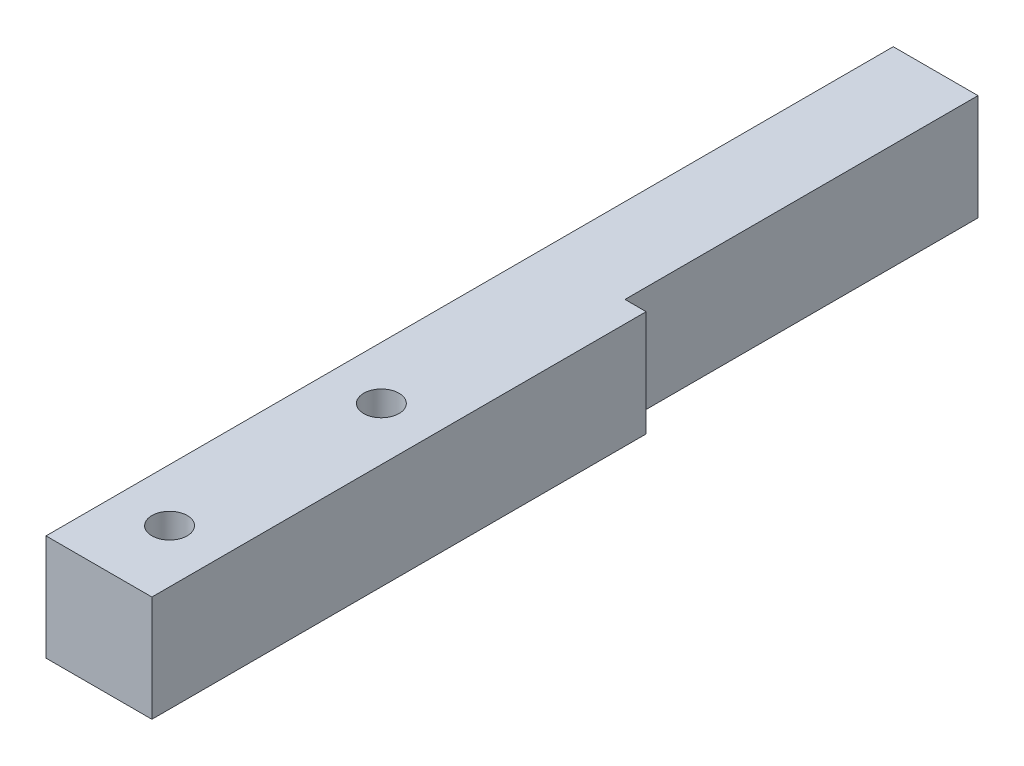
SolidWorks part; units mm, degrees
ref_plane "Front Plane" through (0, 0, 0) normal (0, 0, 1) x (1, 0, 0)
ref_plane "Top Plane" through (0, 0, 0) normal (0, 1, 0) x (1, 0, 0)
ref_plane "Right Plane" through (0, 0, 0) normal (1, 0, 0) x (0, 0, -1)
sketch "Sketch1" plane through (0, 0, 0) normal (0, 0, 1) x (1, 0, 0)
  line L1 (-9.525, -9.525) -> (9.525, -9.525)
  line L2 (-9.525, -9.525) -> (-9.525, 9.525)
  line L3 (-9.525, 9.525) -> (9.525, 9.525)
  line L4 (9.525, -9.525) -> (9.525, 9.525)
  line L5 (-9.525, -9.525) -> (9.525, 9.525) construction
  line L6 (-9.525, 9.525) -> (9.525, -9.525) construction
  point P0 (0, 0)
  dimension "D1" = 19.05
  dimension "D2" = 19.05
extrude "Boss-Extrude1" add sketch "Sketch1" along normal blind 152.4
sketch "Sketch3" plane through (0, -9.525, 0) normal (0, -1, 0) x (1, 0, 0)
  line L0 (-9.525, 152.4) -> (-9.525, 0) construction
  line L1 (-9.525, 152.4) -> (9.525, 152.4) construction
  line L2 (9.525, 63.5) -> (5.715, 63.5)
  line L3 (9.525, 152.4) -> (9.525, 0) construction
  line L4 (5.715, 63.5) -> (5.715, 0)
  line L5 (-9.525, 0) -> (9.525, 0) construction
  line L6 (9.525, 63.5) -> (9.525, 0)
  line L7 (9.525, 0) -> (5.715, 0)
  circle A0 centre (0, 139.7) radius 3.175
  circle A1 centre (0, 101.6) radius 3.175
  point P19 (-319.0492, 143.3675)
  dimension "D1" = 6.35
  dimension "D2" = 9.525
  dimension "D3" = 12.7
  dimension "D4" = 38.1
  dimension "D5" = 3.81
  dimension "D6" = 38.1
extrude "Cut-Extrude1" cut sketch "Sketch3" against normal blind 25.4
